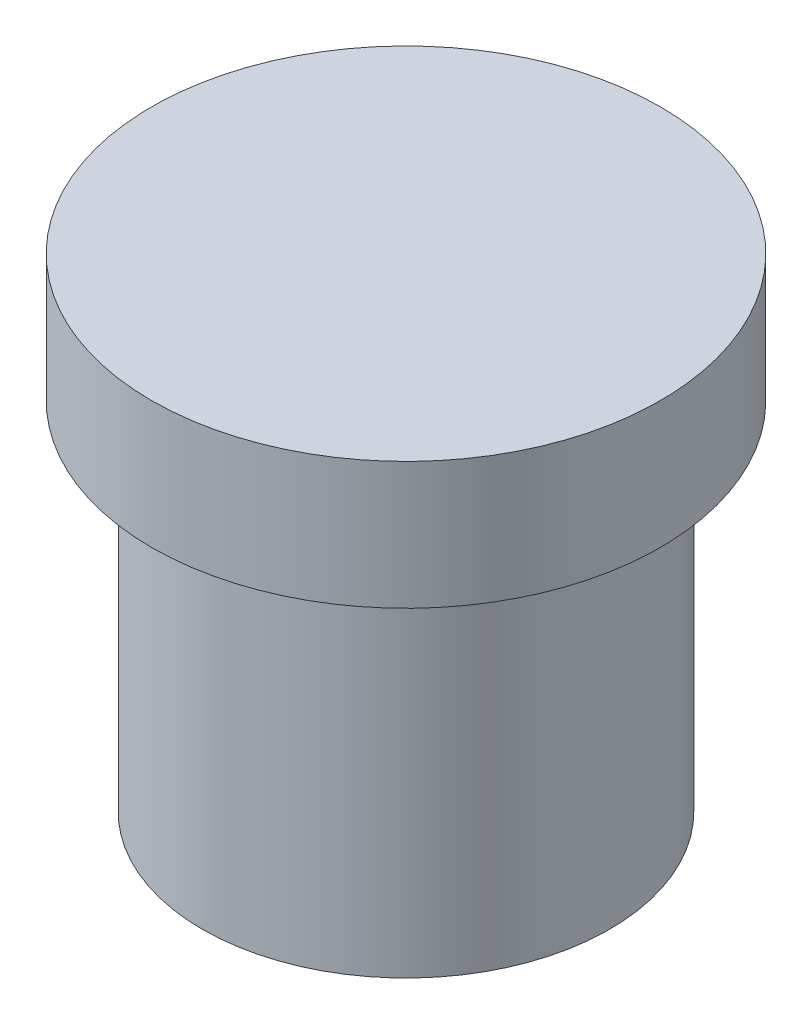
SolidWorks part; units mm, degrees
ref_plane "Front" through (0, 0, 0) normal (0, 0, 1) x (1, 0, 0)
ref_plane "Top" through (0, 0, 0) normal (0, 1, 0) x (1, 0, 0)
ref_plane "Right" through (0, 0, 0) normal (1, 0, 0) x (0, 0, -1)
sketch "Sketch1" plane through (0, 0, 0) normal (0, 1, 0) x (1, 0, 0)
  circle A0 centre (0, 0) radius 400
extrude "Boss-Extrude1" add sketch "Sketch1" along normal blind 700
sketch "Sketch2" plane through (0, 700, 0) normal (0, 1, 0) x (1, 0, 0)
  circle A0 centre (0, 0) radius 500
extrude "Boss-Extrude2" add sketch "Sketch2" along normal blind 250
